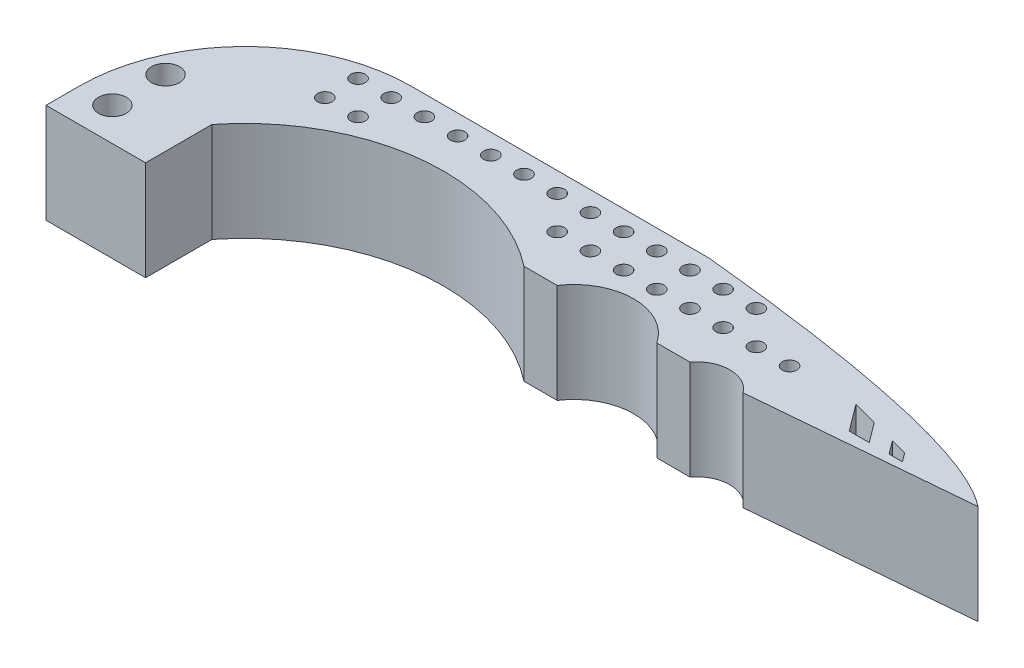
SolidWorks part; units mm, degrees
ref_plane "前视基准面" through (0, 0, 0) normal (0, 0, 1) x (1, 0, 0)
ref_plane "上视基准面" through (0, 0, 0) normal (0, 1, 0) x (1, 0, 0)
ref_plane "右视基准面" through (0, 0, 0) normal (1, 0, 0) x (0, 0, -1)
other "Configuration Table"
sketch "草图1" plane through (0, 0, 0) normal (0, 1, 0) x (1, 0, 0)
  line L0 (0, 0) -> (55, 0)
  line L1 (55, 0) -> (110, 0) construction
  line L2 (110, 0) -> (110, -15) construction
  line L3 (55, 0) -> (105, -5) construction
  line L4 (105, -5) -> (110, -15) construction
  line L5 (110, -15) -> (75, -15)
  line L6 (75, -15) -> (67, -15) construction
  line L7 (67, -15) -> (62, -15)
  line L8 (62, -15) -> (47, -15)
  line L9 (47, -15) -> (42, -15)
  line L10 (0, 0) -> (0, -20) construction
  line L12 (0, 0) -> (-15, 0)
  line L13 (0, 0) -> (0, -30)
  line L14 (0, -30) -> (-15, -30)
  line L15 (-15, 0) -> (-15, -30)
  arc A0 (47, -15) -> (62, -15) centre (54.5, -19.9749) cw
  arc A1 (67, -15) -> (75, -15) centre (71, -18) cw
  arc A2 (0, -20) -> (42, -15) centre (23.5153, -38.6287) cw
  spline S0 degree 2 poles (55, 0) (105, -5) (110, -15) knots 0 0 0 1 1 1
  point P3 (71, -15)
  dimension "D9" = 15
  dimension "D12" = 5
  dimension "D13" = 30
  dimension "D11" = 15
  dimension "D10" = 20
  dimension "D1" = 55
  dimension "D2" = 55
  dimension "D3" = 5
  dimension "D4" = 5
  dimension "D5" = 15
  dimension "D6" = 35
  dimension "D7" = 8
  dimension "D8" = 5
extrude "凸台-拉伸1" add sketch "草图1" along normal blind 15 contours S0 L0 L13 A2 L9 A0 L7 A1 L5 | L12 L15 L14 L13
sketch "草图2" plane through (0, 15, 0) normal (0, 1, 0) x (1, 0, 0)
  line L0 (-15, 0) -> (55, 0) construction
  line L1 (85, -8) -> (55, -8) construction
  line L2 (85, -8) -> (85, -12) construction
  line L3 (85, -12) -> (100, -12) construction
  line L4 (100, -12) -> (85, -8) construction
  line L5 (88, -12) -> (85, -8)
  line L6 (91, -12) -> (88, -12)
  line L7 (91, -12) -> (88.75, -9)
  line L8 (94, -12) -> (92.5, -10)
  line L9 (96, -12) -> (95, -10.6667)
  line L10 (95, -10.6667) -> (92.5, -10)
  line L11 (94, -12) -> (96, -12)
  line L12 (88.75, -9) -> (85, -8)
  line L13 (-15, 0) -> (-15, -30) construction
  line L14 (0, -30) -> (-15, -30) construction
  circle A0 centre (5, -3) radius 1.1
  circle A1 centre (10, -3) radius 1.1
  circle A2 centre (15, -3) radius 1.1
  circle A3 centre (20, -3) radius 1.1
  circle A4 centre (25, -3) radius 1.1
  circle A5 centre (30, -3) radius 1.1
  circle A6 centre (35, -3) radius 1.1
  circle A7 centre (40, -3) radius 1.1
  circle A8 centre (45, -3) radius 1.1
  circle A9 centre (50, -3) radius 1.1
  circle A10 centre (55, -3) radius 1.1
  circle A11 centre (60, -3) radius 1.1
  circle A12 centre (5, -8) radius 1.1
  circle A13 centre (10, -8) radius 1.1
  circle A14 centre (45, -8) radius 1.1
  circle A15 centre (50, -8) radius 1.1
  circle A16 centre (55, -8) radius 1.1
  circle A17 centre (60, -8) radius 1.1
  circle A18 centre (65, -3) radius 1.1
  circle A19 centre (65, -8) radius 1.1
  circle A20 centre (70, -8) radius 1.1
  circle A21 centre (75, -8) radius 1.1
  circle A22 centre (-10, -25) radius 2.1
  circle A24 centre (-10, -17) radius 2.1
  circle A25 centre (40, -8) radius 1.1
  point P5 (88, -12)
  point P40 (85, -12)
  point P41 (85, -12)
  point P42 (91, -12)
  point P43 (94, -12)
  point P44 (96, -12)
  point P52 (-10, -25)
  dimension "D1" = 3
  dimension "D3" = 2
  dimension "D16" = 8
  dimension "D18" = 5
  dimension "D4" = 30
  dimension "D5" = 4
  dimension "D6" = 15
  dimension "D7" = 3
  dimension "D8" = 3
  dimension "D9" = 3
  dimension "D10" = 2
  dimension "D11" = 2
  dimension "D14" = 5
  dimension "D15" = 5
  dimension "D17" = 20
  dimension "D19" = 2
  dimension "D2" = 12
  dimension "D12" = 2
  dimension "D13" = 3
extrude "切除-拉伸1" cut sketch "草图2" against normal up to surface (15 mm away) up to face at (36.3154, 0, 13.4376)
fillet "圆角2" radius 25 1 edges at (-15, 7.5, 0)
sketch "草图4" plane through (0, 15, 0) normal (0, 1, 0) x (1, 0, 0)
  line L0 (75, -15) -> (107.539, -12.1532)
  line L1 (110, -15) -> (75, -15) construction
  line L2 (75, -15) -> (110, -15)
  line L3 (110, -15) -> (110, -12.1532)
  line L4 (110, -12.1532) -> (107.539, -12.1532)
  parabola Q0 (55, 0) -> (110, -15) focus (108.1098, -17.0122) apex (110.5257, -16.7438) construction
  dimension "D1" = 5
extrude "切除-拉伸2" cut sketch "草图4" against normal up to next
